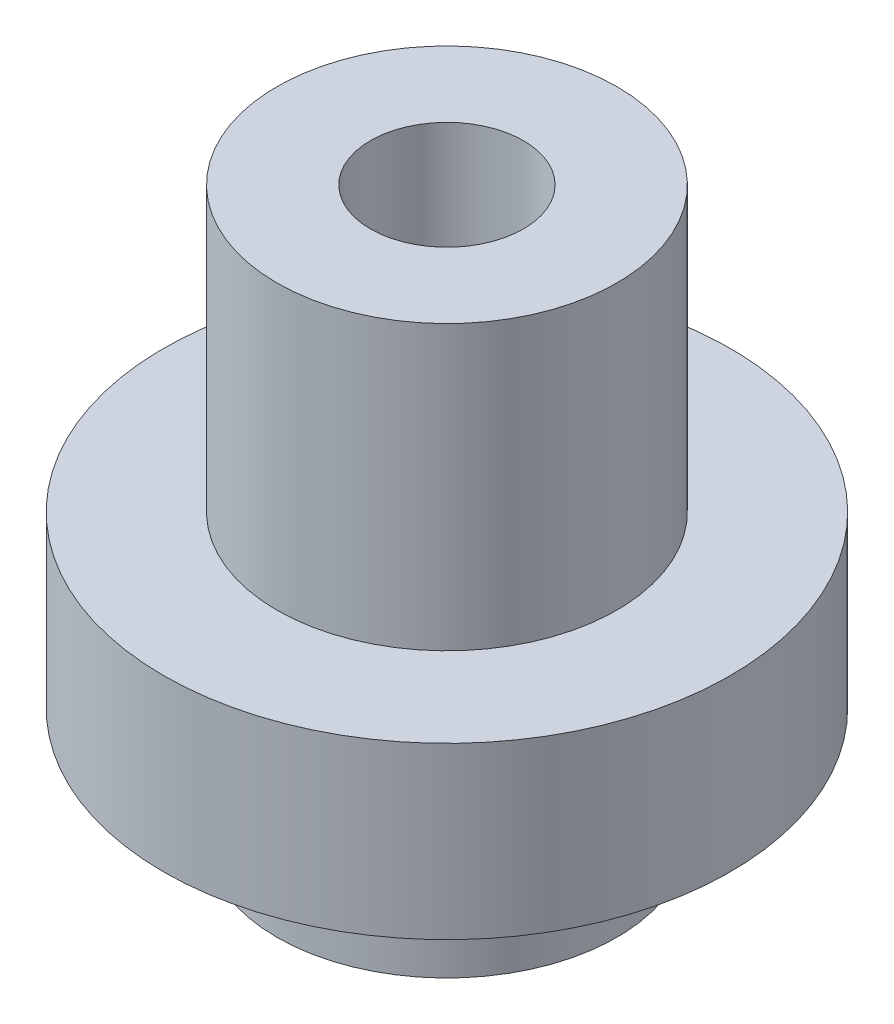
SolidWorks part; units mm, degrees
ref_plane "前基準面" through (0, 0, 0) normal (0, 0, 1) x (1, 0, 0)
ref_plane "上基準面" through (0, 0, 0) normal (0, 1, 0) x (1, 0, 0)
ref_plane "右基準面" through (0, 0, 0) normal (1, 0, 0) x (0, 0, -1)
sketch "草圖1" plane through (0, 0, 0) normal (1, 0, 0) x (0, 0, -1)
  line L0 (0, 0) -> (3, 0)
  line L1 (3, 0) -> (3, 2)
  line L2 (3, 2) -> (5, 2)
  line L3 (5, 2) -> (5, 5)
  line L4 (5, 5) -> (3, 5)
  line L5 (3, 5) -> (3, 10)
  line L6 (3, 10) -> (0, 10)
  line L7 (0, 10) -> (0, 0)
  dimension "D1" = 3
  dimension "D2" = 2
  dimension "D3" = 3
  dimension "D4" = 5
  dimension "D5" = 5
  dimension "D6" = 3
revolve "旋轉1" add sketch "草圖1" angle 360 about L7
hole_wizard "Ø2.7 (2.7) 直徑孔1" positions "草圖2" profile "草圖4" hole size "Ø2.7" standard "ISO" end condition through all
sketch "草圖2" plane through (0, 10, 0) normal (0, 1, 0) x (1, 0, 0)
  point P0 (0, 0)
sketch "草圖4" plane through (0, 10, 0) normal (1, 0, 0) x (0, 0, 1)
  line L0 (0, 0) -> (0, 10)
  line L1 (0, 10) -> (1.35, 10)
  line L2 (1.35, 10) -> (1.35, 0)
  line L5 (1.35, 0) -> (0, 0)
  line L11 (0, -6.35) -> (0, 107.95) construction
  dimension "貫穿孔直徑" = 2.7
  dimension "貫穿孔深度" = 10
